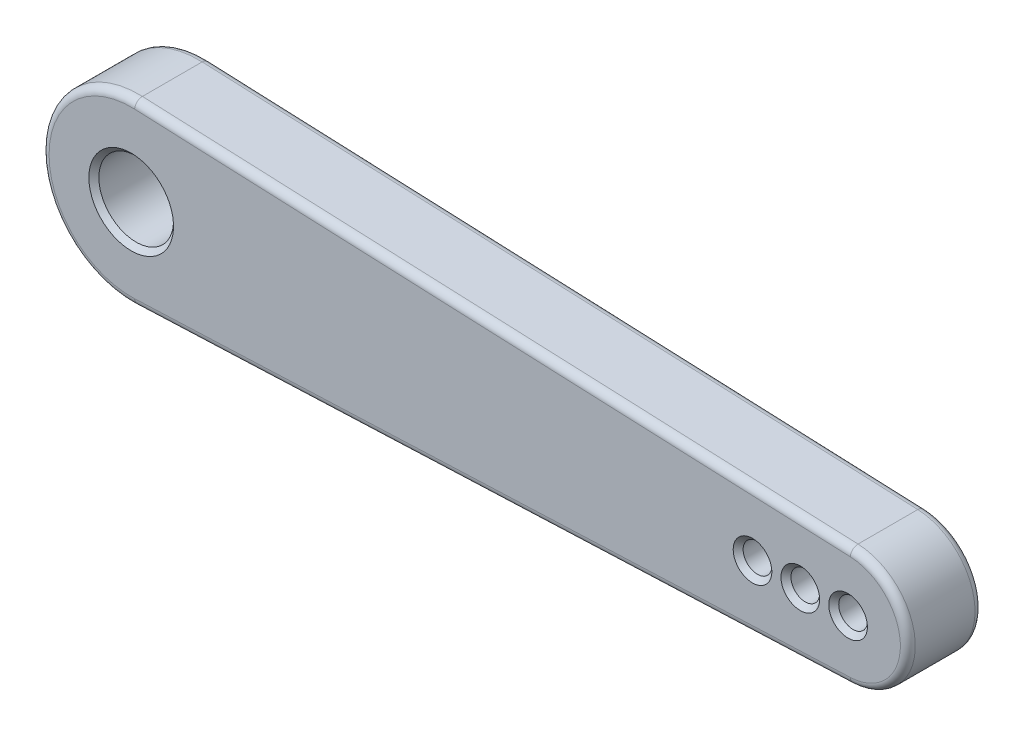
SolidWorks part; units mm, degrees
ref_plane "Front Plane" through (0, 0, 0) normal (0, 0, 1) x (1, 0, 0)
ref_plane "Top Plane" through (0, 0, 0) normal (0, 1, 0) x (1, 0, 0)
ref_plane "Right Plane" through (0, 0, 0) normal (1, 0, 0) x (0, 0, -1)
sketch "Sketch1" plane through (0, 0, 0) normal (0, 0, 1) x (1, 0, 0)
  line L0 (-37.7031, 9.5167) -> (38.3646, 6.3445)
  line L2 (38.3646, -6.3445) -> (-37.7031, -9.5167)
  line L3 (-38.1, 0) -> (0, 0) construction
  line L4 (0, 0) -> (38.1, 0) construction
  circle A2 centre (-38.1, 0) radius 3.9688
  circle A3 centre (38.1, 0) radius 1.524
  circle A4 centre (33.02, 0) radius 1.524
  circle A5 centre (27.94, 0) radius 1.524
  arc A6 (38.3646, 6.3445) -> (38.3646, -6.3445) centre (38.1, 0) cw
  arc A7 (-37.7031, -9.5167) -> (-37.7031, 9.5167) centre (-38.1, 0) cw
  dimension "D2" = 7.9375
  dimension "D3" = 9.525
  dimension "D4" = 3.048
  dimension "D6" = 6.35
  dimension "D1" = 76.2
  dimension "D7" = 5.08
  dimension "D5" = 3
extrude "Boss-Extrude1" add sketch "Sketch1" along normal blind 7.9375
fillet "Fillet2" radius 0.7937 8 edges at (44.45, 0, 0) (0.3307, -7.9306, 0) (-47.625, 0, 0) (44.45, 0, 7.9375) (0.3307, -7.9306, 7.9375) (-47.625, 0, 7.9375) (0.3307, 7.9306, 0) (0.3307, 7.9306, 7.9375)
chamfer "Chamfer1" distance 0.5292 angle 45 8 edges at (39.624, 0, 0) (39.624, 0, 7.9375) (34.544, 0, 0) (34.544, 0, 7.9375) (29.464, 0, 0) (29.464, 0, 7.9375) (-34.1312, 0, 0) (-34.1312, 0, 7.9375)
